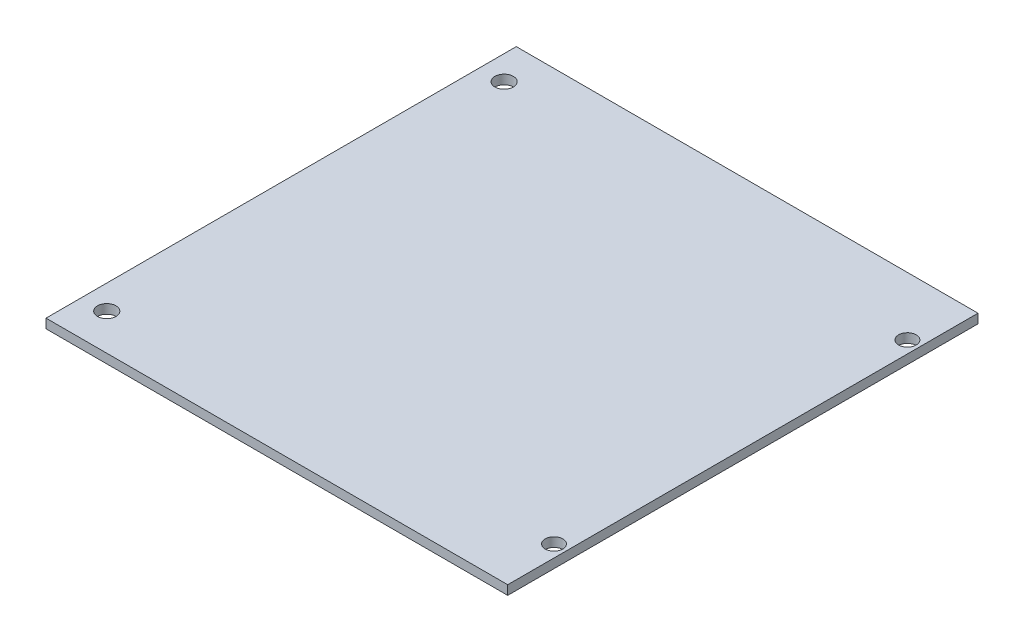
SolidWorks part; units mm, degrees
ref_plane "Front Plane" through (0, 0, 0) normal (0, 0, 1) x (1, 0, 0)
ref_plane "Top Plane" through (0, 0, 0) normal (0, 1, 0) x (1, 0, 0)
ref_plane "Right Plane" through (0, 0, 0) normal (1, 0, 0) x (0, 0, -1)
sketch "Sketch1" plane through (0, 0, 0) normal (0, 1, 0) x (1, 0, 0)
  line L1 (-71.8575, -79.0505) -> (7.9425, -79.0505)
  line L2 (-71.8575, -79.0505) -> (-71.8575, 2.2295)
  line L3 (-71.8575, 2.2295) -> (7.9425, 2.2295)
  line L4 (7.9425, -79.0505) -> (7.9425, 2.2295)
  line L5 (-71.8575, -79.0505) -> (7.9425, 2.2295) construction
  line L6 (-71.8575, 2.2295) -> (7.9425, -79.0505) construction
  point P4 (-31.9575, -38.4105)
  dimension "D1" = 79.8
  dimension "D2" = 81.28
extrude "Boss-Extrude1" add sketch "Sketch1" along normal blind 1.6
sketch "Sketch2" plane through (0, 1.6, 0) normal (0, 1, 0) x (1, 0, 0)
  line L1 (7.9425, -79.0505) -> (7.9425, 2.2295) construction
  line L2 (-71.8575, -79.0505) -> (7.9425, -79.0505) construction
  circle A0 centre (5.8425, -68.9505) radius 1.524
  dimension "D1" = 2.1
  dimension "D2" = 10.1
ref_plane "Plane1" through (0, 0, 38.4105) normal (0, 0, 1) x (1, 0, 0)
ref_plane "Plane3" through (-31.9575, 0, 0) normal (-1, 0, 0) x (0, 0, 1)
extrude "Cut-Extrude1" cut sketch "Sketch2" against normal through all
mirror "Mirror1" about plane through (0, 0, 38.4105) normal (0, 0, 1) of "Cut-Extrude1"
sketch "Sketch4" plane through (0, 0, 0) normal (0, -1, 0) x (1, 0, 0)
  line L0 (-71.8575, 79.0505) -> (7.9425, 79.0505) construction
  line L1 (-71.8575, -2.2295) -> (-71.8575, 79.0505) construction
  circle A0 centre (-67.6575, 72.7505) radius 1.6
  dimension "D1" = 6.3
  dimension "D2" = 4.2
extrude "Cut-Extrude2" cut sketch "Sketch4" against normal through all
mirror "Mirror2" about plane through (0, 0, 38.4105) normal (0, 0, 1) of "Cut-Extrude2"
equation "\"MDF\"= 4.8mm"
equation "\"Foamcore\"= 4.6mm"
equation "\"PCB\" = 1.6mm"
equation "\"GMaterial\"= \"MDF\""
equation "\"BaseWidth\" = 10in"
equation "\"SkidLength\" = 1in"
equation "\"SkidClearance\" = 0.4in"
equation "\"MotorMountLength\" = 2in"
equation "\"MotorMountWidth\" = \"GMaterial\""
equation "\"MotorMountHeight\" = 2.25in"
equation "\"UnoStackWidth\" = 77.4mm"
equation "\"UnoStackLength\" = 79.8mm"
equation "\"UnoStackHeight\" = 34.2mm"
equation "\"D1@Sketch1\"=\"UnoStackLength\""
equation "\"D1@Boss-Extrude1\"=\"PCB\""
